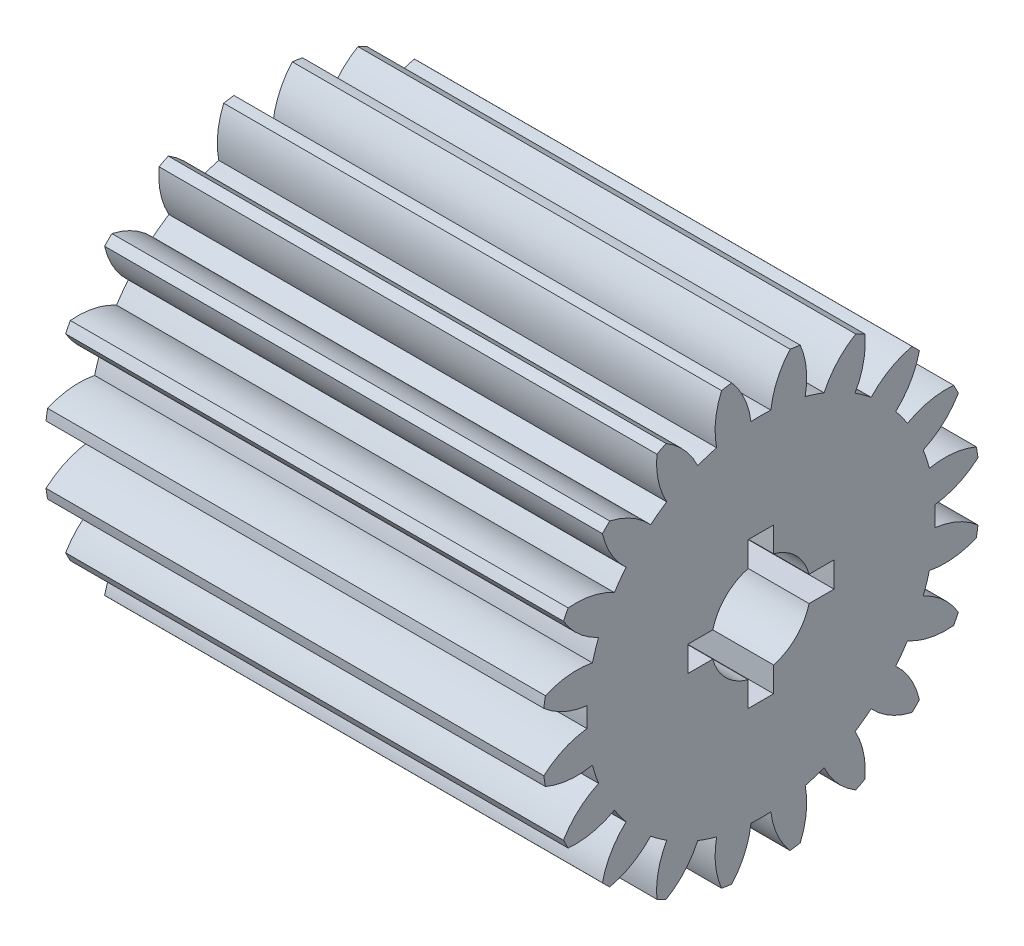
SolidWorks part; units mm, degrees
material "AISI 1020"
ref_plane "Plane1" through (0, 0, 0) normal (0, 0, 1) x (1, 0, 0)
ref_plane "Plane2" through (0, 0, 0) normal (0, 1, 0) x (1, 0, 0)
ref_plane "Plane3" through (0, 0, 0) normal (1, 0, 0) x (0, 0, -1)
other "Configuration Table"
sketch "HoldingSke" plane through (0, 0, 0) normal (0, 1, 0) x (1, 0, 0)
  line L0 (0, 0) -> (2.3492, -0.8551)
  line L1 (-15, 0) -> (100, 0) construction
  line L2 (0, 0) -> (-2.1039, 2.3779)
  line L3 (0, 0) -> (-11.863, 4.5341)
  line L4 (0, 0) -> (8.1152, 2.9537)
  line L5 (0, 0) -> (-46.8476, -17.4728)
  line L6 (0, 0) -> (-8.2896, -5.593)
  line L7 (-2.1039, 2.3779) -> (8.6586, 51.2059)
  line L8 (-76.2, 54.61) -> (-75.9, 54.61)
  line L9 (-71.009, 38.7566) -> (-53.1078, 45.2721)
  line L10 (-76.2, 71.12) -> (104.1128, 71.12)
  line L11 (0, 0) -> (-10, 0)
  line L12 (-76.2, 101.6) -> (-76.185, 101.6)
  line L13 (24.9733, 27.94) -> (52.9518, 28.4284)
  line L14 (24.9733, 27.94) -> (24.9743, 27.94)
  line L15 (24.9733, 27.94) -> (100.4006, 29.5858)
  line L16 (-63.627, -0.4) -> (-12.827, -0.4)
  circle A0 centre (0, 0) radius 1
  circle A1 centre (0, 0) radius 3.499
  circle A2 centre (0, 0) radius 37.5
  circle A3 centre (0, 0) radius 1
  dimension "MHD" = 6.998
  dimension "Hub_dia" = 75
  dimension "Bore" = 2
  dimension "MBD" = 2
  dimension "Num_teeth" = 20
  dimension "Pitch" = 2.5
  dimension "Overall_len" = 50
  dimension "Show_teeth" = 20
  dimension "Thickness" = 10
  dimension "OAL" = 50.0001
  dimension "T_dim" = 0.3
  dimension "Ap" = 20
  dimension "H" = 19.05
  dimension "Pitch_radius" = 180.3128
  dimension "Width" = 10
  dimension "Backlash" = 0.015
  dimension "Addendum_fac" = 1
  dimension "Dedendum_fac" = 1.25
  dimension "Clearance_fac" = 0.25
  dimension "Dedendum_add" = 0.001
  dimension "Module" = 0.4
sketch "BasProSke" plane through (0, 0, 0) normal (0, 1, 0) x (1, 0, 0)
  line L0 (-10, 0) -> (60, 0) construction
  line L1 (0, 0) -> (0, 4.4)
  line L2 (0, 0) -> (10, 0)
  line L3 (10, 0) -> (10, 4.4)
  line L4 (10, 4.4) -> (0, 4.4)
  dimension "Thickness" = 10
  dimension "Diameter" = 8.8
revolve "Base-Revolve" add sketch "BasProSke" angle 360 about L0
sketch "TooCutSke" plane through (0, 0, 0) normal (1, 0, 0) x (0, 0, -1)
  line L1 (0, 0) -> (0, 107) construction
  line L2 (0, 0) -> (-0.3401, 3.9855) construction
  line L3 (0, 0) -> (-1.2482, 7.8811) construction
  line L4 (-0.3401, 3.9855) -> (-0.6241, 3.9405) construction
  arc A0 (0.1996, 3.4933) -> (-0.1996, 3.4933) centre (0, 0) ccw
  arc A1 (0.606, 4.3837) -> (-0.606, 4.3837) centre (0, 0) ccw
  circle A2 centre (0, 0) radius 4 construction
  circle A3 centre (0, 0) radius 3.7588 construction
  arc A4 (-0.1996, 3.4933) -> (-0.606, 4.3837) centre (-1.7886, 3.306) ccw
  arc A5 (0.606, 4.3837) -> (0.1996, 3.4933) centre (1.7886, 3.306) ccw
  dimension "Root_dia" = 6.998
  dimension "Overcut_dia" = 8.8508
  dimension "Pitch_dia" = 8
  dimension "Base_dia" = 7.5175
  dimension "Flank_rad" = 1.6
  dimension "Half_ang" = 9
  dimension "Half_CT" = 0.2876
extrude "ToothCut" cut sketch "TooCutSke" along normal through all
fillet "Breaks" [suppressed] radius 0.008
fillet "RootFillets" [suppressed] radius 0.101
pattern_circular "TeethCuts" count 20 every 18 about axis through (-10, 0, 0) along (1, 0, 0) of "ToothCut", "RootFillets", "Breaks"
sketch "HubNeaOneSke" plane through (0, 0, 0) normal (-1, 0, 0) x (0, 0, 1)
  circle A0 centre (0, 0) radius 3.499
  dimension "Diameter" = 6.998
extrude "HubNearOne" [suppressed] add sketch "HubNeaOneSke" along normal blind 40.0001
sketch "HubNeaBotSke" plane through (0, 0, 0) normal (-1, 0, 0) x (0, 0, 1)
  circle A0 centre (0, 0) radius 3.499
  dimension "Diameter" = 6.998
extrude "HubNearBoth" [suppressed] add sketch "HubNeaBotSke" along normal blind 20
ref_plane "FarPln" through (10, 0, 0) normal (1, 0, 0) x (0, 0, -1)
sketch "HubFarSke" plane through (10, 0, 0) normal (1, 0, 0) x (0, 0, -1)
  circle A0 centre (0, 0) radius 3.499
  dimension "Diameter" = 6.998
extrude "HubFar" [suppressed] add sketch "HubFarSke" along normal blind 20
sketch "BorSke" plane through (0, 0, 0) normal (1, 0, 0) x (0, 0, -1)
  circle A0 centre (0, 0) radius 1
  dimension "Diameter" = 2
extrude "Bore" cut sketch "BorSke" along normal mid plane 100.0001
sketch "KeySke" plane through (0, 0, 0) normal (1, 0, 0) x (0, 0, -1)
  line L0 (-0.4, 0) -> (-0.4, 1.3)
  line L1 (-0.4, 1.3) -> (0.4, 1.3)
  line L2 (0.4, 1.3) -> (0.4, 0)
  line L3 (0, 0) -> (0, 34) construction
  line L4 (-0.4, 0) -> (0.4, 0)
  dimension "Offset" = 1.3
  dimension "Width" = 0.8
extrude "Keyway" [suppressed] cut sketch "KeySke" along normal mid plane 100.0001
pattern_circular "Keyway2" [suppressed] count 2 every 90 about axis through (-10, 0, 0) along (1, 0, 0)
sketch "Sketch1" plane through (10, 0, 0) normal (1, 0, 0) x (0, 0, -1)
  line L0 (-0.255, 0.9587) -> (0.255, 0.9587)
  line L1 (-0.255, 0.9587) -> (-0.255, 1.4687)
  line L2 (0.255, 0.9587) -> (0.255, 1.4687)
  line L3 (-0.255, 1.4687) -> (0.255, 1.4687)
  line L4 (0.9587, 0.255) -> (0.9587, -0.255)
  line L5 (0.9587, 0.255) -> (1.4687, 0.255)
  line L6 (0.9587, -0.255) -> (1.4687, -0.255)
  line L7 (1.4687, 0.255) -> (1.4687, -0.255)
  line L8 (0.255, -0.9587) -> (-0.255, -0.9587)
  line L9 (0.255, -0.9587) -> (0.255, -1.4687)
  line L10 (-0.255, -0.9587) -> (-0.255, -1.4687)
  line L11 (0.255, -1.4687) -> (-0.255, -1.4687)
  line L12 (-0.9587, -0.255) -> (-0.9587, 0.255)
  line L13 (-0.9587, -0.255) -> (-1.4687, -0.255)
  line L14 (-0.9587, 0.255) -> (-1.4687, 0.255)
  line L15 (-1.4687, -0.255) -> (-1.4687, 0.255)
  circle A0 centre (0, 0) radius 0.992
  dimension "D2" = 1.984
  dimension "D1" = 0.51
  dimension "D3" = 0.51
  dimension "D4" = 0.51
  dimension "D5" = 0.51
  dimension "D6" = 0.51
  dimension "D7" = 0.51
  dimension "D8" = 0.51
  dimension "D9" = 0.51
extrude "Cut-Extrude1" cut sketch "Sketch1" against normal blind 100 contours L3 L2 L0 L1 | L5 L7 L6 L4 | L9 L11 L10 L8 | L13 L15 L14 L12
equation "' \"Module@HoldingSke\" = 6.35"
equation "' \"Num_teeth@HoldingSke\" = 12"
equation "' \"Ap@HoldingSke\" =  20"
equation "' \"Ap@HoldingSke\" = 20"
equation "' \"Width@HoldingSke\" = 0.5 * 25.4"
equation "' \"Hub_dia@HoldingSke\"= 1 * 25.4"
equation "' \"Hub_dia@HoldingSke\" = 1 * 25.4"
equation "' \"Overall_len@HoldingSke\" = 1.0 * 25.4"
equation "' \"Bore@HoldingSke\" = 0.75 * 25.4"
equation "' \"T_dim@HoldingSke\" = 0.1 * 25.4"
equation "' \"Width@KeySke\" = 0.25 * 25.4"
equation "' \"Show_teeth@HoldingSke\" = 13"
equation "' \"Backlash@HoldingSke\" = 0.009 * 25.4"
equation "' \"Addendum_fac@HoldingSke\" = 1.0"
equation "' \"Dedendum_fac@HoldingSke\" = 1.25"
equation "' \"Dedendum_add@HoldingSke\" = 0.00005 * 25.4"
equation "' \"Clearance_fac@HoldingSke\" = 0.25"
equation "\"Pitch@HoldingSke\" = 1 / \"Module@HoldingSke\""
equation "\"Overcut_dia@TooCutSke\" = (\"Num_teeth@HoldingSke\" + 2 * \"Addendum_fac@HoldingSke\") / \"Pitch@HoldingSke\" + 0.002 * 25.4"
equation "\"Pitch_dia@TooCutSke\" = \"Num_teeth@HoldingSke\" / \"Pitch@HoldingSke\""
equation "\"Base_dia@TooCutSke\" = \"Num_teeth@HoldingSke\" / \"Pitch@HoldingSke\" * cos((\"Ap@HoldingSke\"  * 3.14159265 / 180))"
equation "\"Root_dia@TooCutSke\" = (\"Num_teeth@HoldingSke\" + 2) / \"Pitch@HoldingSke\" - 2 * (\"Addendum_fac@HoldingSke\" + \"Dedendum_fac@HoldingSke\") / \"Pitch@HoldingSke\" - \"Dedendum_add@HoldingSke\" * 2"
equation "\"Half_ang@TooCutSke\" = 180 / \"Num_teeth@HoldingSke\""
equation "\"Half_CT@TooCutSke\" = \"Num_teeth@HoldingSke\" / \"Pitch@HoldingSke\" * sin((3.14159265 / 2 / \"Num_teeth@HoldingSke\")) / 2 - 7 * \"Backlash@HoldingSke\" / 4"
equation "\"Flank_rad@TooCutSke\" = \"Num_teeth@HoldingSke\" / \"Pitch@HoldingSke\" / 5"
equation "\"Radius@RootFillets\" = \"Clearance_fac@HoldingSke\" / \"Pitch@HoldingSke\" + \"Dedendum_add@HoldingSke\""
equation "\"Break_rad@Breaks\" = 0.02 / \"Pitch@HoldingSke\""
equation "\"Thickness@HoldingSke\" = \"Width@HoldingSke\""
equation "\"OAL@HoldingSke\" = \"Thickness@HoldingSke\""
equation "\"MHD@HoldingSke\" = (\"Num_teeth@HoldingSke\" + 2) / \"Pitch@HoldingSke\" - 2 * (\"Addendum_fac@HoldingSke\" + \"Dedendum_fac@HoldingSke\")  / \"Pitch@HoldingSke\" - \"Dedendum_add@HoldingSke\" * 2"
equation "\"MBD@HoldingSke\" = (\"Num_teeth@HoldingSke\" + 2) / \"Pitch@HoldingSke\" - 2 * (\"Addendum_fac@HoldingSke\" + \"Dedendum_fac@HoldingSke\")  / \"Pitch@HoldingSke\" - \"Dedendum_add@HoldingSke\" * 2 - 0.002 * 25.4"
equation "\"MHD@HoldingSke\" = ((sgn( \"MHD@HoldingSke\" - \"Hub_dia@HoldingSke\" )-1)*( \"MHD@HoldingSke\" - \"Hub_dia@HoldingSke\" ))/-2+ \"Hub_dia@HoldingSke\""
equation "\"MBD@HoldingSke\" = ((sgn( \"MBD@HoldingSke\" - \"Bore@HoldingSke\" )-1)*( \"MBD@HoldingSke\" - \"Bore@HoldingSke\" ))/-2+ \"Bore@HoldingSke\""
equation "\"OAL@HoldingSke\" = ((sgn( \"OAL@HoldingSke\" - \"Overall_len@HoldingSke\" )+1)*( \"OAL@HoldingSke\" - \"Overall_len@HoldingSke\" ))/2 + \"Overall_len@HoldingSke\" + 0.000002 * 25.4"
equation "\"Num_teeth@TeethCuts\" = int( \"Show_teeth@HoldingSke\" ) + 1"
equation "\"Num_teeth@TeethCuts\" = ((sgn( \"Num_teeth@TeethCuts\" - \"Num_teeth@HoldingSke\" )-1)*( \"Num_teeth@TeethCuts\" - \"Num_teeth@HoldingSke\" ))/-2+ \"Num_teeth@HoldingSke\""
equation "\"Num_teeth@TeethCuts\" = ((sgn( \"Num_teeth@TeethCuts\" - 2.0)+1)*( \"Num_teeth@TeethCuts\" - 2.0))/2 +2.0"
equation "\"Angle@TeethCuts\" = 360.0 / \"Num_teeth@HoldingSke\""
equation "\"Diameter@BasProSke\" = (\"Num_teeth@HoldingSke\" + 2 * \"Addendum_fac@HoldingSke\") / \"Pitch@HoldingSke\""
equation "\"Thickness@BasProSke\"  = \"Thickness@HoldingSke\""
equation "' \"Fillet_rad@BasProSke\" =  \"Thickness@HoldingSke\" * 0.05"
equation "' \"Fillet_rad@BasProSke\" = \"Thickness@HoldingSke\" * 0.05"
equation "\"MHD@HoldingSke\" = ((sgn( \"MHD@HoldingSke\" - \"Root_dia@TooCutSke\" )-1)*( \"MHD@HoldingSke\" - \"Root_dia@TooCutSke\" ))/-2+ \"Root_dia@TooCutSke\""
equation "\"Diameter@HubNeaOneSke\" = \"MHD@HoldingSke\""
equation "\"Length@HubNearOne\" = \"OAL@HoldingSke\" - \"Thickness@BasProSke\""
equation "\"Diameter@HubNeaBotSke\" = \"MHD@HoldingSke\""
equation "\"Length@HubNearBoth\" = ( \"OAL@HoldingSke\" - \"Thickness@BasProSke\" ) / 2.0"
equation "\"Thickness@FarPln\" = \"Thickness@BasProSke\""
equation "\"Diameter@HubFarSke\" = \"MHD@HoldingSke\""
equation "\"Length@HubFar\" = ( \"OAL@HoldingSke\" - \"Thickness@BasProSke\" ) / 2.0"
equation "\"Diameter@BorSke\" = \"MBD@HoldingSke\""
equation "\"D1@Bore\" = \"OAL@HoldingSke\" * 2.0"
equation "\"D1@Keyway\" = \"OAL@HoldingSke\" * 2.0"
equation "\"Offset@KeySke\" = \"T_dim@HoldingSke\" + \"MBD@HoldingSke\" / 2.0"
